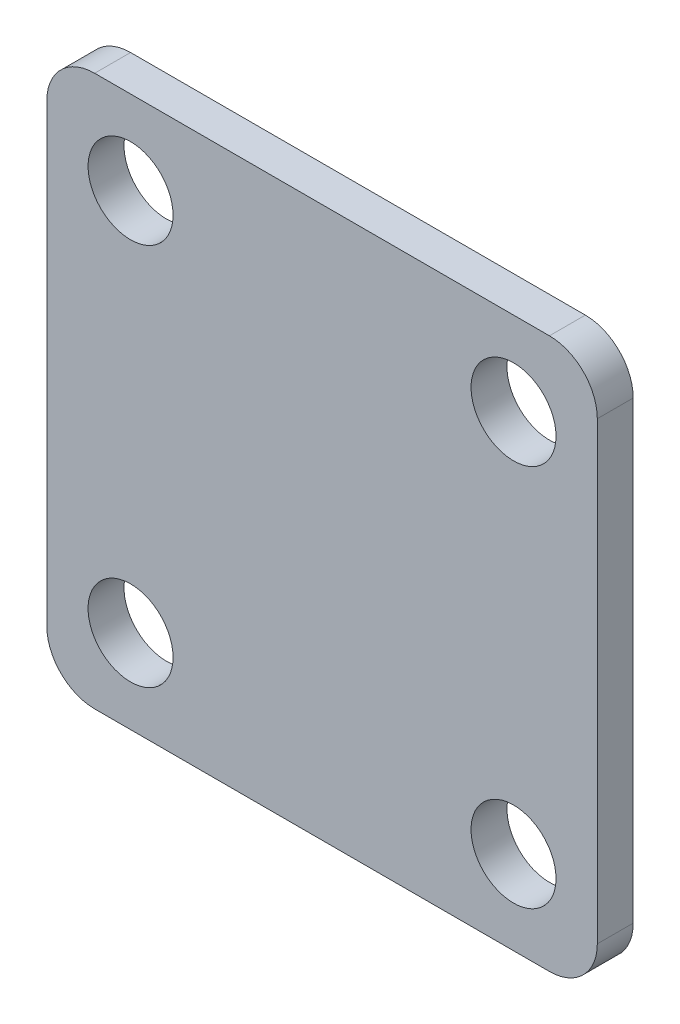
SolidWorks part; units mm, degrees
material "PCB"
ref_plane "Front Plane" through (0, 0, 0) normal (0, 0, 1) x (1, 0, 0)
ref_plane "Top Plane" through (0, 0, 0) normal (0, 1, 0) x (1, 0, 0)
ref_plane "Right Plane" through (0, 0, 0) normal (1, 0, 0) x (0, 0, -1)
sketch "Sketch1" plane through (0, 0, 0) normal (0, 0, 1) x (1, 0, 0)
  line L1 (-9.5, 11.5) -> (9.5, 11.5)
  line L2 (-11.5, 9.5) -> (-11.5, -9.5)
  line L3 (-9.5, -11.5) -> (9.5, -11.5)
  line L4 (11.5, 9.5) -> (11.5, -9.5)
  line L5 (-11.5, 11.5) -> (11.5, -11.5) construction
  line L6 (-11.5, -11.5) -> (11.5, 11.5) construction
  arc A0 (-11.5, -9.5) -> (-9.5, -11.5) centre (-9.5, -9.5) ccw
  arc A1 (9.5, -11.5) -> (11.5, -9.5) centre (9.5, -9.5) ccw
  arc A2 (9.5, 11.5) -> (11.5, 9.5) centre (9.5, 9.5) cw
  arc A3 (-9.5, 11.5) -> (-11.5, 9.5) centre (-9.5, 9.5) ccw
  circle A4 centre (-8, 8) radius 1.775
  circle A5 centre (8, 8) radius 1.775
  circle A6 centre (8, -8) radius 1.775
  circle A7 centre (-8, -8) radius 1.775
  point P0 (0, 0)
  point P26 (0, 0)
  point P27 (0, 0)
  point P28 (0, 0)
  point P29 (0, 0)
  dimension "D3" = 2
  dimension "D8" = 3.55
  dimension "D1" = 23
  dimension "D2" = 23
  dimension "D4" = 16
  dimension "D5" = 16
  dimension "D6" = 16
  dimension "D7" = 16
extrude "Boss-Extrude1" add sketch "Sketch1" along normal blind 1.5
